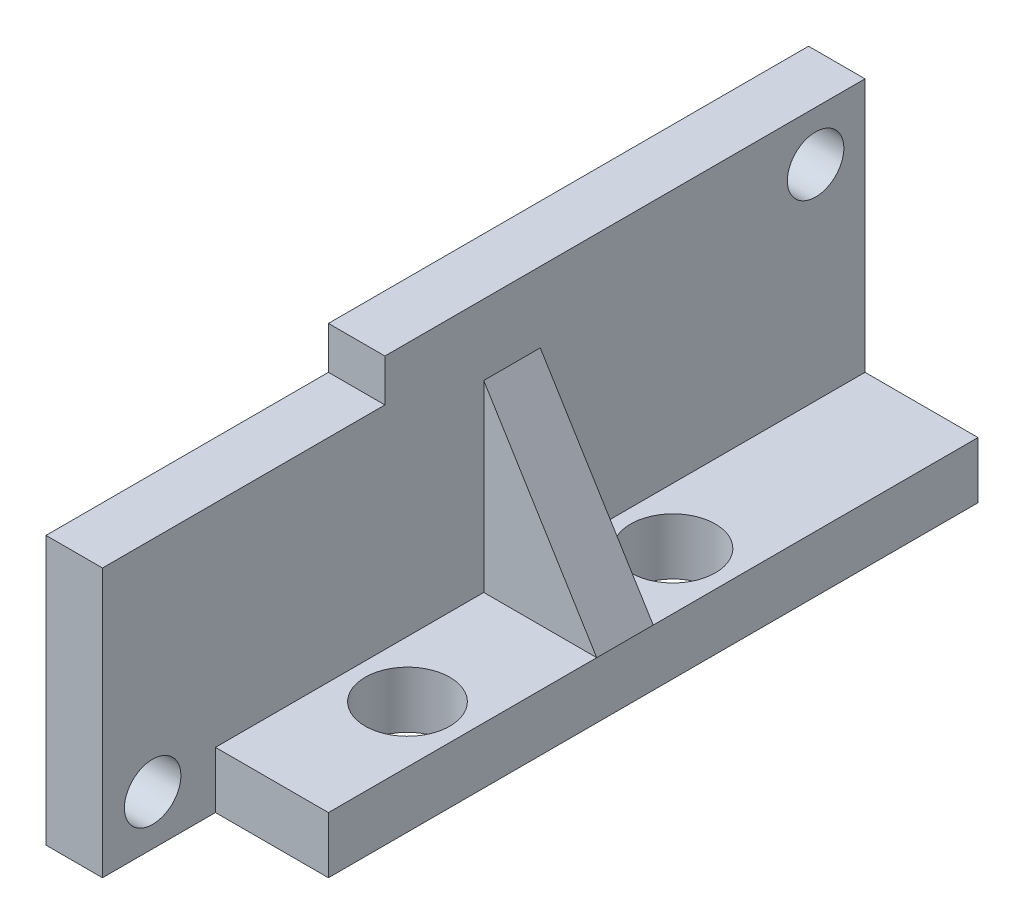
SolidWorks part; units mm, degrees
ref_plane "Front Plane" through (0, 0, 0) normal (0, 0, 1) x (1, 0, 0)
ref_plane "Top Plane" through (0, 0, 0) normal (0, 1, 0) x (1, 0, 0)
ref_plane "Right Plane" through (0, 0, 0) normal (1, 0, 0) x (0, 0, -1)
sketch "Sketch1" plane through (0, 0, 0) normal (0, 0, 1) x (1, 0, 0)
  line L0 (0, 11) -> (0, 0)
  line L1 (0, 0) -> (6, 0)
  line L2 (6, 0) -> (6, 2)
  line L3 (6, 2) -> (2, 2)
  line L4 (2, 2) -> (2, 11)
  line L5 (2, 11) -> (0, 11)
  dimension "D1" = 2
  dimension "D2" = 2
  dimension "D3" = 11
  dimension "D4" = 6
extrude "Boss-Extrude1" add sketch "Sketch1" along normal mid plane 27
sketch "Sketch2" plane through (2, 0, 0) normal (1, 0, 0) x (0, 0, -1)
  line L0 (-13.5, 11) -> (-13.5, 9.5)
  line L1 (-13.5, 2) -> (-13.5, 11) construction
  line L2 (-13.5, 9.5) -> (-3.5, 9.5)
  line L3 (-3.5, 9.5) -> (-3.5, 11)
  line L4 (-13.5, 11) -> (13.5, 11) construction
  line L5 (-13.5, 11) -> (-3.5, 11)
  dimension "D1" = 1.5
  dimension "D2" = 10
extrude "Cut-Extrude1" cut sketch "Sketch2" against normal blind 27
sketch "Sketch3" plane through (0, 0, 0) normal (-1, 0, 0) x (0, 0, 1)
  line L0 (13.5, 0) -> (-13.5, 0) construction
  line L2 (13.5, 9.5) -> (13.5, 0) construction
  circle A0 centre (-11.75, 9.25) radius 1
  circle A2 centre (11.7238, 1.75) radius 1
  dimension "D1" = 2
  dimension "D2" = 1.7762
  dimension "D3" = 1.75
extrude "Cut-Extrude2" cut sketch "Sketch3" against normal blind 3.6
sketch "Sketch6" plane through (0, 0, -13.5) normal (0, 0, -1) x (-1, 0, 0)
  line L0 (-6, 2) -> (0, 2)
  line L1 (0, 11) -> (0, 0) construction
  line L2 (0, 2) -> (0, 0)
  line L3 (0, 0) -> (-6, 0)
  line L4 (-6, 0) -> (-6, 2)
extrude "Boss-Extrude2" add sketch "Sketch6" along normal blind 3
sketch "Sketch7" plane through (0, 2, 0) normal (0, 1, 0) x (1, 0, 0)
  line L0 (4, -13.5) -> (4, 16.5) construction
  line L1 (6, -13.5) -> (2, -13.5) construction
  line L2 (0, 16.5) -> (6, 16.5) construction
  line L3 (0, 0) -> (6, 0) construction
  line L4 (6, -13.5) -> (6, 16.5) construction
  circle A0 centre (4, -4.7) radius 1.5
  circle A2 centre (4, 4.7) radius 1.5
  dimension "D1" = 3
  dimension "D2" = 8.8
extrude "Cut-Extrude5" cut sketch "Sketch7" against normal blind 9
sketch "Sketch9" plane through (0, 0, 0) normal (0, 0, 1) x (1, 0, 0)
  line L0 (2, 8.5) -> (2, 2)
  line L1 (2, 2) -> (2, 11) construction
  line L2 (2, 2) -> (6, 2)
  line L3 (6, 2) -> (2, 8.5)
  dimension "D1" = 6.5
extrude "Boss-Extrude3" add sketch "Sketch9" against normal blind 2
sketch "Sketch10" plane through (0, 2, 0) normal (0, 1, 0) x (1, 0, 0)
  line L0 (0, 13.5) -> (6, 13.5)
  line L1 (6, 2) -> (6, 16.5) construction
  line L2 (6, 13.5) -> (6, 16.5)
  line L3 (6, 16.5) -> (0, 16.5)
  line L4 (0, 16.5) -> (0, 13.5)
extrude "Cut-Extrude6" cut sketch "Sketch10" against normal blind 10
sketch "Sketch11" plane through (0, 2, 0) normal (0, 1, 0) x (1, 0, 0)
  line L0 (2, -13.5) -> (2, -9.5)
  line L1 (2, -10.7555) -> (2, 0) construction
  line L2 (2, -9.5) -> (6, -9.5)
  line L3 (6, -13.5) -> (6, 0) construction
  line L4 (6, -9.5) -> (6, -13.5)
  line L5 (6, -13.5) -> (2, -13.5) construction
  line L6 (6, -13.5) -> (2, -13.5)
  dimension "D1" = 4
extrude "Cut-Extrude7" cut sketch "Sketch11" against normal blind 10
